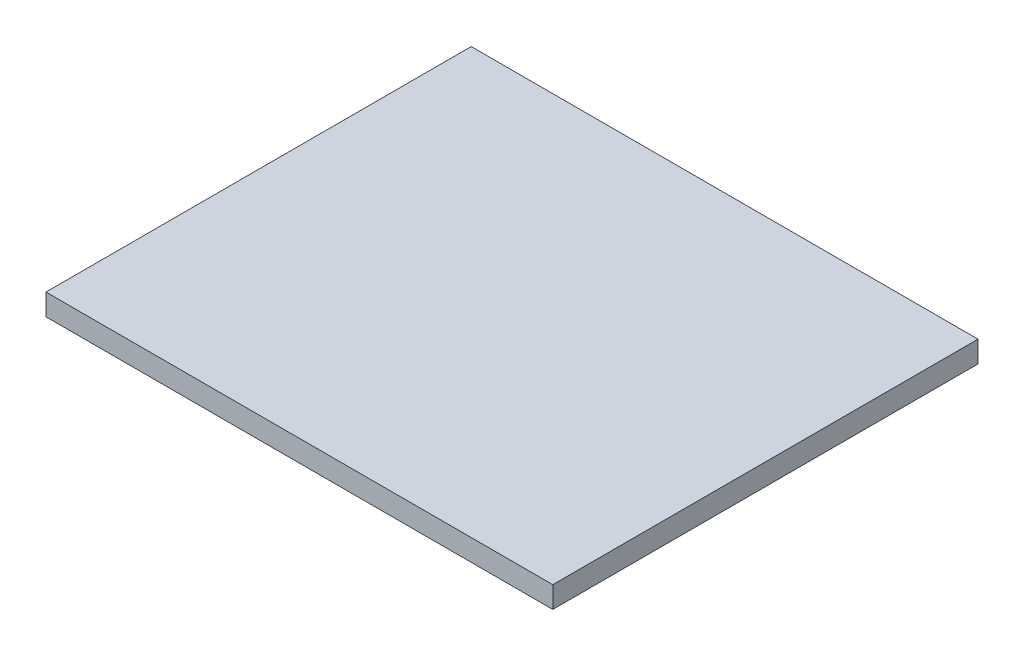
SolidWorks part; units mm, degrees
ref_plane "Front Plane" through (0, 0, 0) normal (0, 0, 1) x (1, 0, 0)
ref_plane "Top Plane" through (0, 0, 0) normal (0, 1, 0) x (1, 0, 0)
ref_plane "Right Plane" through (0, 0, 0) normal (1, 0, 0) x (0, 0, -1)
sketch "Sketch1" plane through (0, 0, 0) normal (0, 1, 0) x (1, 0, 0)
  line L6 (-29.5, 24.75) -> (29.5, 24.75)
  line L28 (-29.5, 24.75) -> (-29.5, -24.75)
  line L29 (-29.5, -24.75) -> (29.5, -24.75)
  line L30 (29.5, 24.75) -> (29.5, -24.75)
  line L31 (-29.5, 24.75) -> (29.5, -24.75) construction
  line L32 (-29.5, -24.75) -> (29.5, 24.75) construction
  circle A1 centre (0, 0) radius 3
  point P0 (0, 0)
  dimension "D3" = 6
  dimension "D1" = 59
  dimension "D2" = 49.5
extrude "Boss-Extrude1" add sketch "Sketch1" along normal blind 1.5
sketch "Sketch2" plane through (0, 0, -24.75) normal (0, 0, -1) x (-1, 0, 0)
  line L0 (-29.5, 1.5) -> (-29.5, 0) construction
  line L1 (-29.5, 1.5) -> (29.5, 1.5)
  line L2 (-29.5, 1.5) -> (-29.5, 2.5)
  line L4 (29.5, 1.5) -> (29.5, 2.5)
  line L5 (-1.18, 2.5) -> (0, 4)
  line L6 (0, 55) -> (0, -55) construction
  line L7 (1.18, 2.5) -> (0, 4)
  line L8 (1.18, 2.5) -> (2.36, 4)
  line L9 (3.54, 2.5) -> (2.36, 4)
  line L10 (3.54, 2.5) -> (4.72, 4)
  line L11 (5.9, 2.5) -> (4.72, 4)
  line L12 (5.9, 2.5) -> (7.08, 4)
  line L13 (8.26, 2.5) -> (7.08, 4)
  line L14 (8.26, 2.5) -> (9.44, 4)
  line L15 (10.62, 2.5) -> (9.44, 4)
  line L16 (10.62, 2.5) -> (11.8, 4)
  line L17 (12.98, 2.5) -> (11.8, 4)
  line L18 (12.98, 2.5) -> (14.16, 4)
  line L19 (15.34, 2.5) -> (14.16, 4)
  line L20 (15.34, 2.5) -> (16.52, 4)
  line L21 (17.7, 2.5) -> (16.52, 4)
  line L22 (17.7, 2.5) -> (18.88, 4)
  line L23 (20.06, 2.5) -> (18.88, 4)
  line L24 (20.06, 2.5) -> (21.24, 4)
  line L25 (22.42, 2.5) -> (21.24, 4)
  line L26 (22.42, 2.5) -> (23.6, 4)
  line L27 (24.78, 2.5) -> (23.6, 4)
  line L28 (24.78, 2.5) -> (25.96, 4)
  line L29 (27.14, 2.5) -> (25.96, 4)
  line L30 (27.14, 2.5) -> (28.32, 4)
  line L31 (29.5, 2.5) -> (28.32, 4)
  line L32 (-29.5, 2.5) -> (-28.32, 4)
  line L33 (-27.14, 2.5) -> (-28.32, 4)
  line L34 (-27.14, 2.5) -> (-25.96, 4)
  line L35 (-24.78, 2.5) -> (-25.96, 4)
  line L36 (-24.78, 2.5) -> (-23.6, 4)
  line L37 (-22.42, 2.5) -> (-23.6, 4)
  line L38 (-22.42, 2.5) -> (-21.24, 4)
  line L39 (-20.06, 2.5) -> (-21.24, 4)
  line L40 (-20.06, 2.5) -> (-18.88, 4)
  line L41 (-17.7, 2.5) -> (-18.88, 4)
  line L42 (-17.7, 2.5) -> (-16.52, 4)
  line L43 (-15.34, 2.5) -> (-16.52, 4)
  line L44 (-15.34, 2.5) -> (-14.16, 4)
  line L45 (-12.98, 2.5) -> (-14.16, 4)
  line L46 (-12.98, 2.5) -> (-11.8, 4)
  line L47 (-10.62, 2.5) -> (-11.8, 4)
  line L48 (-10.62, 2.5) -> (-9.44, 4)
  line L49 (-8.26, 2.5) -> (-9.44, 4)
  line L50 (-8.26, 2.5) -> (-7.08, 4)
  line L51 (-5.9, 2.5) -> (-7.08, 4)
  line L52 (-5.9, 2.5) -> (-4.72, 4)
  line L53 (-3.54, 2.5) -> (-4.72, 4)
  line L54 (-3.54, 2.5) -> (-2.36, 4)
  line L55 (-1.18, 2.5) -> (-2.36, 4)
  dimension "D1" = 1
  dimension "D2" = 1.5
  dimension "D3" = 13
extrude "Boss-Extrude2" add sketch "Sketch2" against normal up to surface (49.5 mm away) up to face at (0, 0.75, 24.75)
sketch "Sketch3" plane through (0, 0, 0) normal (0, -1, 0) x (-1, 0, 0)
  line L0 (0, 55) -> (0, -55) construction
  line L2 (-1.75, -2.4367) -> (-1.75, -5)
  line L3 (-1.75, -5) -> (1.75, -5)
  line L4 (1.75, -2.4367) -> (1.75, -5)
  arc A0 (1.75, -2.4367) -> (-1.75, -2.4367) centre (0, 0) ccw
  dimension "D2" = 6
  dimension "D1" = 3.5
  dimension "D3" = 5
  dimension "D4" = 1.75
extrude "Cut-Extrude1" cut sketch "Sketch3" against normal blind 2
sketch "Sketch4" plane through (29.5, 0, 0) normal (1, 0, 0) x (0, 0, -1)
  line L1 (-24.75, 4) -> (-24.75, 2.5) construction
  line L2 (-24.75, 4) -> (24.75, 4) construction
  line L3 (-24, 4) -> (-24.75, 4)
  line L4 (-24.75, 4) -> (-24.75, 3.25)
  arc A0 (-24.75, 3.25) -> (-24, 4) centre (-24, 3.25) cw
extrude "Cut-Extrude3" cut sketch "Sketch4" against normal through all
mirror "Mirror1" about plane through (0, 0, 0) normal (0, 0, 1) of "Cut-Extrude3"
sketch "Sketch5" plane through (0, 2, 0) normal (0, -1, 0) x (1, 0, 0)
  circle A0 centre (0, 0) radius 3
  dimension "D1" = 6
extrude "Boss-Extrude3" [suppressed] add sketch "Sketch5" along normal blind 0.5
sketch "Sketch6" [suppressed] plane through (0, 2, 0) normal (0, -1, 0) x (1, 0, 0)
  line L1 (1.75, 5) -> (-1.75, 5)
  line L2 (1.75, 5) -> (1.75, 2.4367)
  line L3 (1.75, 2.4367) -> (-1.75, 2.4367)
  line L4 (-1.75, 5) -> (-1.75, 2.4367)
  point P5 (0, 0)
  point P6 (0, 0)
  point P7 (-1.75, 2.4367)
extrude "Cut-Extrude4" [suppressed] cut sketch "Sketch6" against normal blind 0.5
chamfer "Chamfer3" distance 1.5 angle 45 1 edges at (0, 0, 5)
sketch "Sketch7" plane through (0, 0, 24.75) normal (0, 0, 1) x (1, 0, 0)
  line L1 (-29.5, 2.5) -> (29.5, 2.5)
  line L2 (-29.5, 2.5) -> (-29.5, 4.5865)
  line L3 (-29.5, 4.5865) -> (29.5, 4.5865)
  line L4 (29.5, 2.5) -> (29.5, 4.5865)
extrude "Cut-Extrude5" cut sketch "Sketch7" against normal through all
